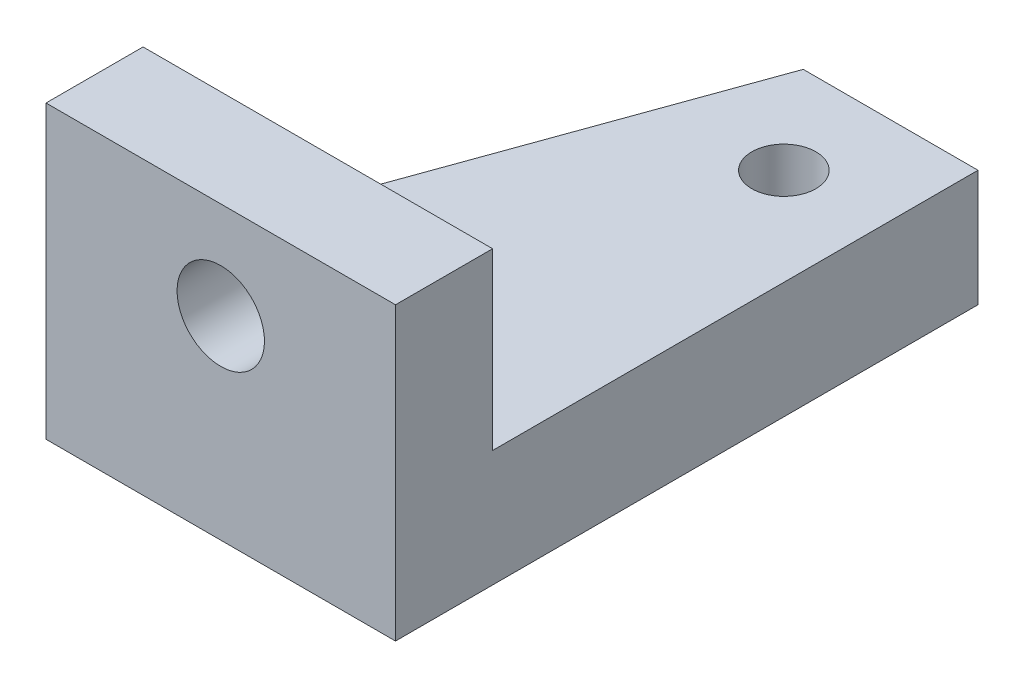
SolidWorks part; units mm, degrees
material "6061 合金"
ref_plane "前视基准面" through (0, 0, 0) normal (0, 0, 1) x (1, 0, 0)
ref_plane "上视基准面" through (0, 0, 0) normal (0, 1, 0) x (1, 0, 0)
ref_plane "右视基准面" through (0, 0, 0) normal (1, 0, 0) x (0, 0, -1)
sketch "草图1" plane through (0, 0, 0) normal (1, 0, 0) x (0, 0, -1)
  line L0 (0, 0) -> (0, 15)
  line L1 (0, 15) -> (5, 15)
  line L2 (5, 15) -> (5, 6)
  line L3 (5, 6) -> (30, 6)
  line L4 (30, 6) -> (30, 0)
  line L5 (30, 0) -> (0, 0)
  dimension "D1" = 6
  dimension "D2" = 5
  dimension "D3" = 30
  dimension "D4" = 15
extrude "凸台-拉伸1" add sketch "草图1" along normal mid plane 18
hole_wizard "M4 螺纹孔1" positions "草图3" profile "草图2" tap size "M4" standard "GB" end condition up to next
sketch "草图3" plane through (0, 0, 0) normal (0, -1, 0) x (-1, 0, 0)
  line L1 (-9, 30) -> (9, 30) construction
  line L2 (-9, 0) -> (-9, 30) construction
  point P0 (-4, 25)
  dimension "D1" = 5
  dimension "D2" = 5
sketch "草图2" plane through (4, 0, -25) normal (1, 0, 0) x (0, 0, -1)
  line L0 (0, 0) -> (0, 6)
  line L1 (0, 6) -> (1.65, 6)
  line L2 (1.65, 6) -> (1.65, 0)
  line L5 (1.65, 0) -> (0, 0)
  line L11 (0, -6.35) -> (0, 107.95) construction
  dimension "螺纹线主直径" = 3.3
  dimension "通孔螺纹孔钻头深度" = 6
sketch "草图4" plane through (0, 0, 0) normal (0, -1, 0) x (1, 0, 0)
  line L0 (0, -30) -> (-9, -5)
  line L1 (9, -30) -> (-9, -30) construction
  line L2 (-9, 0) -> (-9, -30) construction
  line L3 (9, 0) -> (-9, 0) construction
  line L4 (9, 0) -> (9, -30) construction
  dimension "D1" = 5
  dimension "D2" = 9
extrude "切除-拉伸1" cut sketch "草图4" against normal through all and the other way through all
hole_wizard "M4 间隙孔1" positions "草图6" profile "草图5" hole size "M4" standard "GB" end condition up to next
sketch "草图6" plane through (0, 0, -5) normal (0, 0, -1) x (-1, 0, 0)
  line L0 (-9, 15) -> (9, 15) construction
  point P0 (0, 10)
  dimension "D1" = 5
sketch "草图5" plane through (0, 10, -5) normal (1, 0, 0) x (0, 1, 0)
  line L0 (0, 0) -> (0, 5)
  line L1 (0, 5) -> (2.25, 5)
  line L2 (2.25, 5) -> (2.25, 0)
  line L5 (2.25, 0) -> (0, 0)
  line L11 (0, -6.35) -> (0, 107.95) construction
  dimension "通孔孔直径" = 4.5
  dimension "通孔孔深度" = 5
